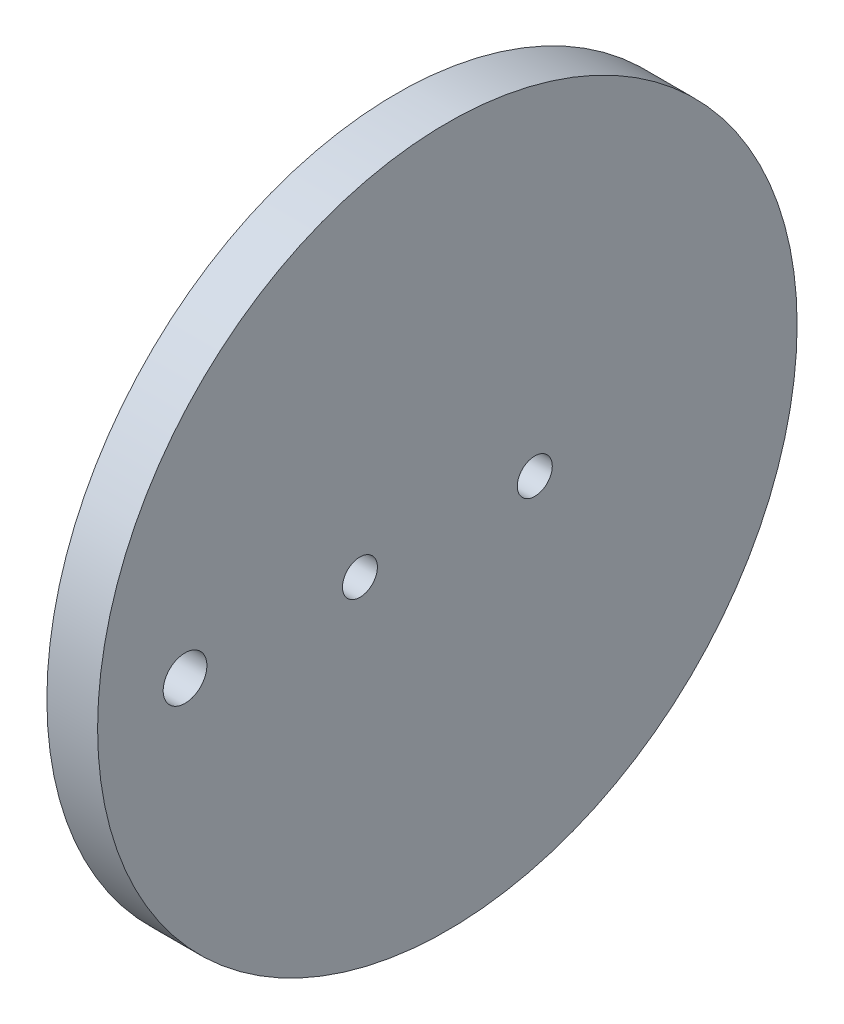
SolidWorks part; units mm, degrees
material "ナイロン"
ref_plane "正面" through (0, 0, 0) normal (0, 0, 1) x (1, 0, 0)
ref_plane "平面" through (0, 0, 0) normal (0, 1, 0) x (1, 0, 0)
ref_plane "右側面" through (0, 0, 0) normal (1, 0, 0) x (0, 0, -1)
sketch "ｽｹｯﾁ1" plane through (0, 0, 0) normal (1, 0, 0) x (0, 0, -1)
  circle A0 centre (0, 0) radius 40
  dimension "D1" = 80
extrude "ﾎﾞｽ - 押し出し1" add sketch "ｽｹｯﾁ1" along normal blind 5.8
sketch "ｽｹｯﾁ2" plane through (5.8, 0, 0) normal (1, 0, 0) x (0, 0, -1)
  line L0 (0, 0) -> (50000, 0) construction
  line L1 (0, 0) -> (0, 50000) construction
  circle A0 centre (10, 0) radius 2
  circle A1 centre (-10, 0) radius 2
  circle A2 centre (-30, 0) radius 2.5
  dimension "D1" = 20
  dimension "D2" = 4
  dimension "D3" = 20
  dimension "D4" = 5
extrude "ｶｯﾄ - 押し出し1" cut sketch "ｽｹｯﾁ2" against normal through all
